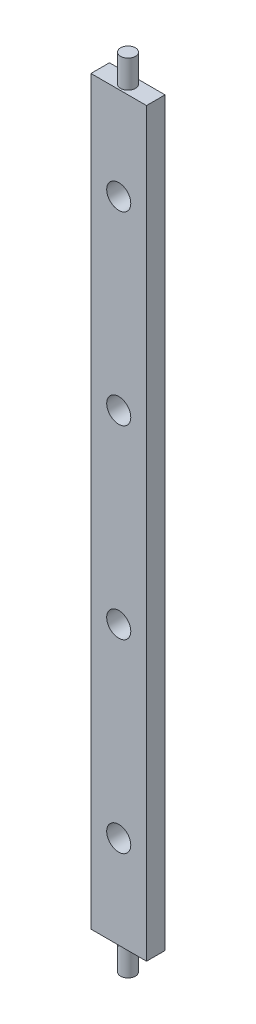
SolidWorks part; units mm, degrees
ref_plane "Front Plane" through (0, 0, 0) normal (0, 0, 1) x (1, 0, 0)
ref_plane "Top Plane" through (0, 0, 0) normal (0, 1, 0) x (1, 0, 0)
ref_plane "Right Plane" through (0, 0, 0) normal (1, 0, 0) x (0, 0, -1)
other "Configuration Table"
sketch "Sketch1" plane through (0, 0, 0) normal (0, 0, 1) x (1, 0, 0)
  line L1 (-3, -40) -> (3, -40)
  line L2 (-3, -40) -> (-3, 40)
  line L3 (-3, 40) -> (3, 40)
  line L4 (3, -40) -> (3, 40)
  line L5 (-3, -40) -> (3, 40) construction
  line L6 (-3, 40) -> (3, -40) construction
extrude "Rod_Bar" add sketch "Sketch1" along normal blind 2
sketch "Sketch2" plane through (0, 0, 0) normal (0, 0, 1) x (1, 0, 0)
  circle A0 centre (0, -30) radius 1.3
  circle A1 centre (0, -10) radius 1.3
  circle A2 centre (0, 10) radius 1.3
  circle A3 centre (0, 30) radius 1.3
extrude "Link_Holes" cut sketch "Sketch2" against normal through all and the other way through all
sketch "Sketch3" plane through (0, 40, 0) normal (0, 1, 0) x (1, 0, 0)
  circle A0 centre (0, -1) radius 0.8
extrude "SMA_Spring_Peg" add sketch "Sketch3" along normal blind 3
sketch "Sketch4" plane through (0, -40, 0) normal (0, -1, 0) x (1, 0, 0)
  circle A0 centre (0, 1) radius 0.8
extrude "Bias_Spring_Peg" add sketch "Sketch4" along normal blind 3
